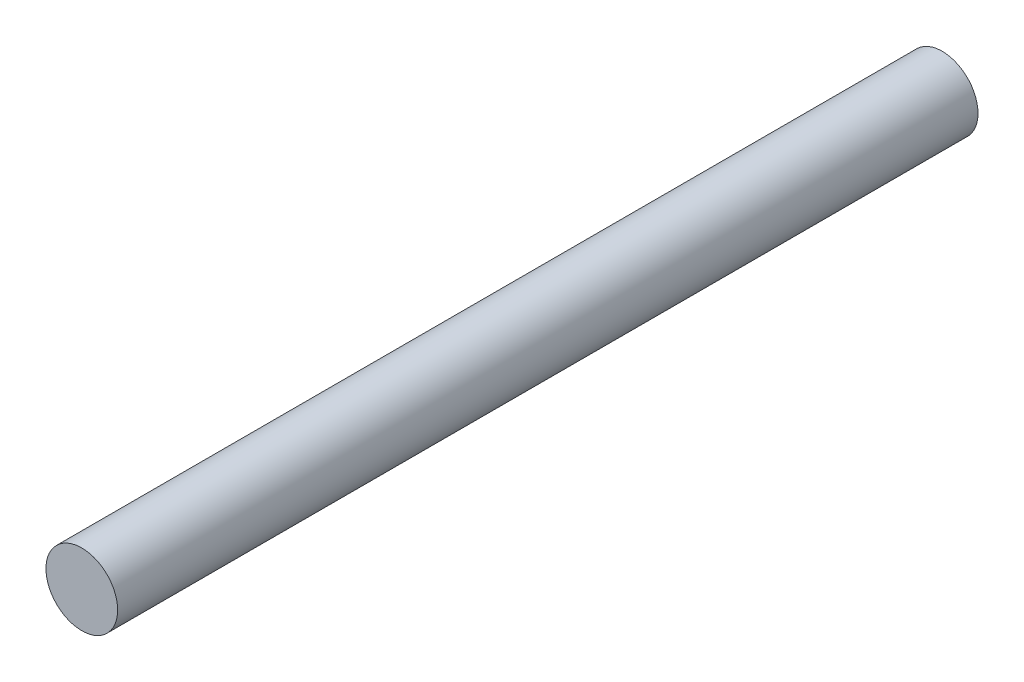
SolidWorks part; units mm, degrees
ref_plane "Plano frontal" through (0, 0, 0) normal (0, 0, 1) x (1, 0, 0)
ref_plane "Plano superior" through (0, 0, 0) normal (0, 1, 0) x (1, 0, 0)
ref_plane "Plano direito" through (0, 0, 0) normal (1, 0, 0) x (0, 0, -1)
sketch "Esboço1" plane through (0, 0, 0) normal (0, 0, 1) x (1, 0, 0)
  circle A0 centre (0, 0) radius 5
  dimension "D1" = 10
extrude "Ressalto-extrusão1" add sketch "Esboço1" along normal mid plane 120 contours A0
